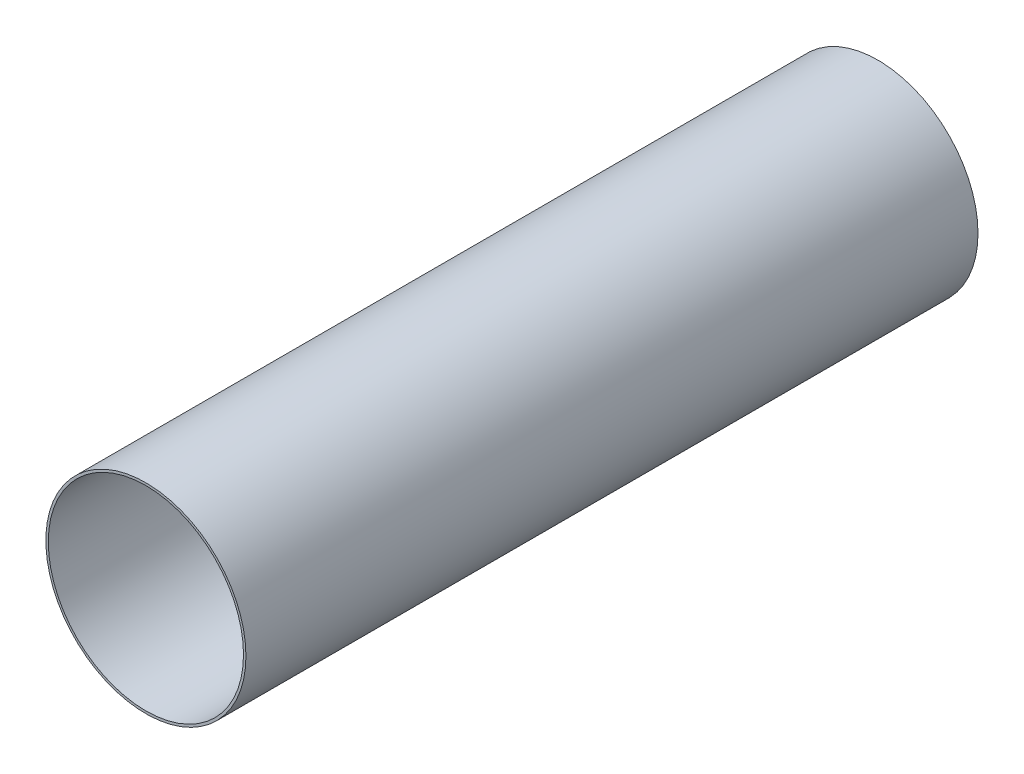
SolidWorks part; units mm, degrees
material "Thornel Mat VMA"
ref_plane "Front Plane" through (0, 0, 0) normal (0, 0, 1) x (1, 0, 0)
ref_plane "Top Plane" through (0, 0, 0) normal (0, 1, 0) x (1, 0, 0)
ref_plane "Right Plane" through (0, 0, 0) normal (1, 0, 0) x (0, 0, -1)
sketch "Sketch1" plane through (0, 0, 0) normal (0, 0, 1) x (1, 0, 0)
  circle A0 centre (0, 0) radius 82
  circle A1 centre (0, 0) radius 80
  dimension "D1" = 160
  dimension "D2" = 164
extrude "Boss-Extrude1" add sketch "Sketch1" along normal mid plane 600
